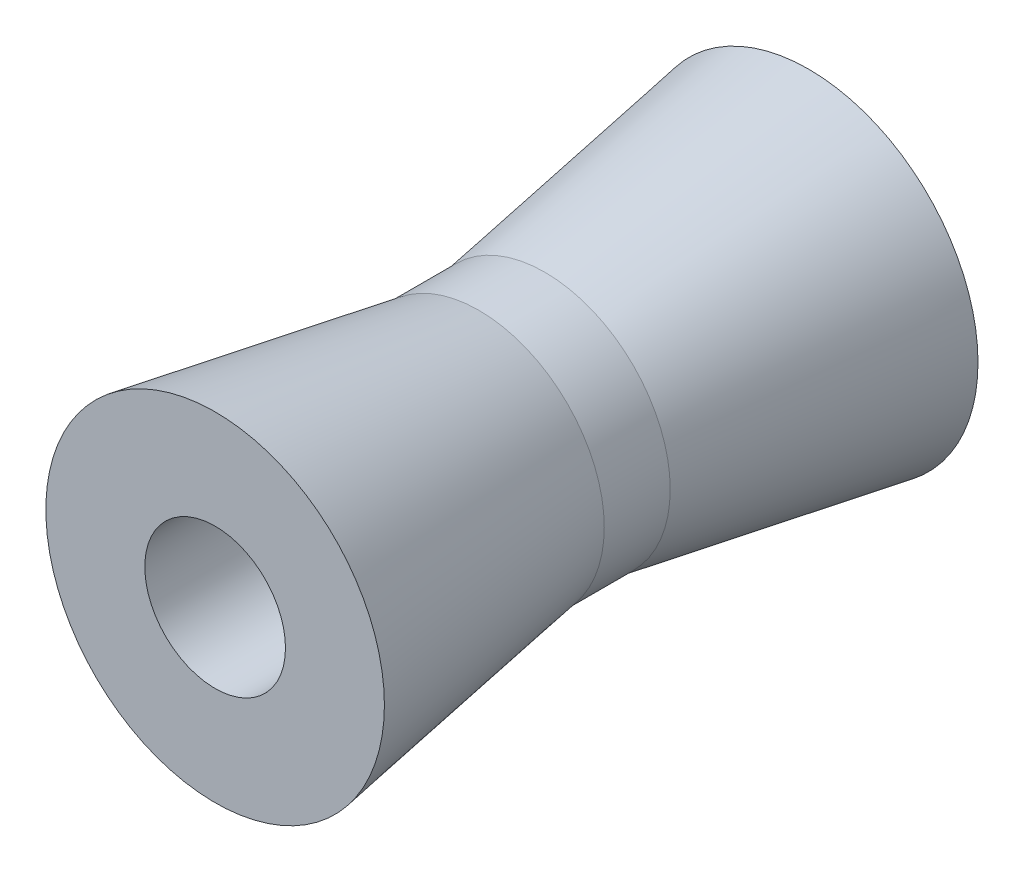
SolidWorks part; units mm, degrees
ref_plane "Plan de face" through (0, 0, 0) normal (0, 0, 1) x (1, 0, 0)
ref_plane "Plan de dessus" through (0, 0, 0) normal (0, 1, 0) x (1, 0, 0)
ref_plane "Plan de droite" through (0, 0, 0) normal (1, 0, 0) x (0, 0, -1)
sketch "Esquisse1" plane through (0, 0, 0) normal (0, 0, 1) x (1, 0, 0)
  circle A1 centre (0, 0) radius 2.032
  circle A2 centre (0, 0) radius 3.6195
  dimension "D1" = 4.064
  dimension "D2" = 1.5875
extrude "Boss.-Extru.1" add sketch "Esquisse1" along normal mid plane 17.145
sketch "Esquisse4" plane through (0, 0, 0) normal (1, 0, 0) x (0, 0, -1)
  line L0 (0.9525, 3.6195) -> (8.5725, 4.8895)
  line L1 (8.5725, 4.8895) -> (8.5725, 3.6195)
  line L2 (8.5725, 3.6195) -> (-8.5725, 3.6195) construction
  line L3 (0.9525, 3.6195) -> (8.5725, 3.6195)
  line L4 (0, 0) -> (8.5725, 0) construction
  line L5 (8.5725, -2.032) -> (8.5725, 2.032) construction
  dimension "D1" = 7.62
  dimension "D2" = 1.27
revolve "Révolution1" add sketch "Esquisse4" angle 360 about L4
mirror "Symétrie1" about plane through (0, 0, 0) normal (0, 0, 1) of "Révolution1"
